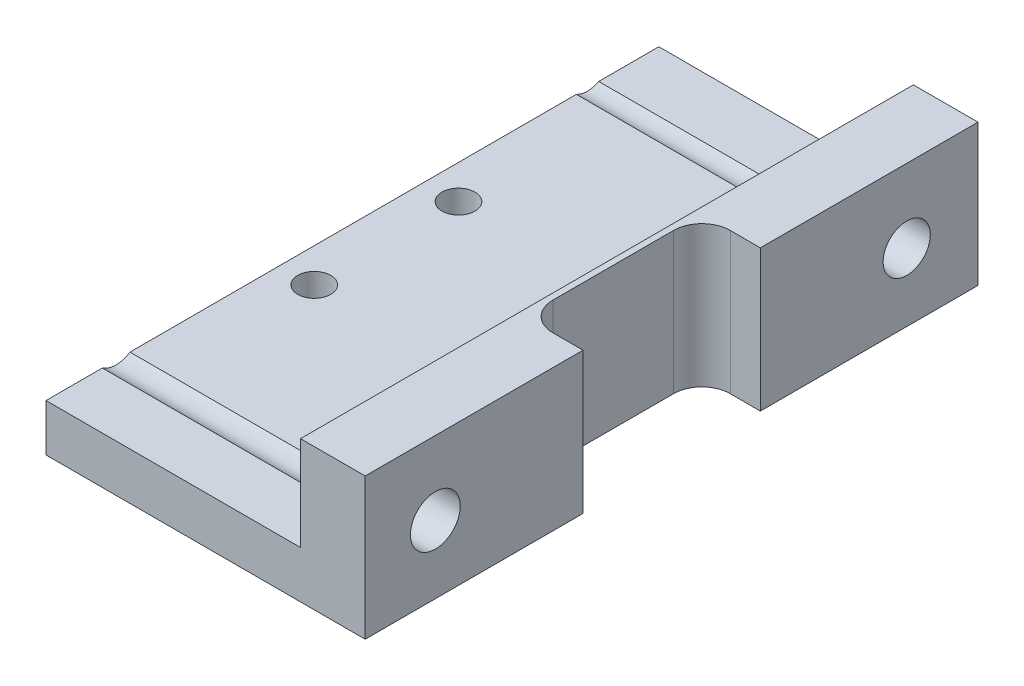
SolidWorks part; units mm, degrees
ref_plane "Alzado" through (0, 0, 0) normal (0, 0, 1) x (1, 0, 0)
ref_plane "Planta" through (0, 0, 0) normal (0, 1, 0) x (1, 0, 0)
ref_plane "Vista lateral" through (0, 0, 0) normal (1, 0, 0) x (0, 0, -1)
sketch "Croquis1" plane through (0, 0, 0) normal (0, 1, 0) x (1, 0, 0)
  line L0 (10.6725, -9.7621) -> (7.4725, -9.7621)
  line L1 (-23.1831, 32.1331) -> (10.6725, 32.1331)
  line L2 (-23.1831, 32.1331) -> (-23.1831, -32.8682)
  line L3 (-23.1831, -32.8682) -> (10.6725, -32.8682)
  line L4 (10.6725, 32.1331) -> (10.6725, 9.0402)
  line L5 (4.4725, -6.7621) -> (4.4725, 6.0505)
  line L6 (7.4822, 9.0505) -> (10.6725, 9.0402)
  line L7 (10.6725, -9.7621) -> (10.6725, -32.8682)
  arc A0 (7.4822, 9.0505) -> (4.4725, 6.0505) centre (7.4725, 6.0505) ccw
  arc A1 (4.4725, -6.7621) -> (7.4725, -9.7621) centre (7.4725, -6.7621) ccw
  dimension "D1" = 3
extrude "Saliente-Extruir1" add sketch "Croquis1" along normal blind 15
sketch "Croquis2" plane through (0, 0, 0) normal (0, -1, 0) x (1, 0, 0)
  line L0 (-23.1831, -32.1331) -> (-23.1831, 32.8682) construction
  line L1 (-23.1831, 0.3676) -> (19.7756, 0.3676) construction
  line L3 (3.8169, -17.1324) -> (-23.1831, -17.1324)
  line L4 (3.8169, -17.1324) -> (3.8169, 17.8676)
  line L5 (3.8169, 17.8676) -> (-23.1831, 17.8676)
  line L6 (-23.1831, -17.1324) -> (-23.1831, 17.8676)
  line L7 (3.8169, -17.1324) -> (-23.1831, 17.8676) construction
  line L8 (3.8169, 17.8676) -> (-23.1831, -17.1324) construction
  circle A0 centre (0.4169, -7.2824) radius 1.75
  circle A1 centre (-19.5831, -7.2824) radius 1.75
  circle A2 centre (-19.5831, 8.0176) radius 1.75
  circle A3 centre (0.4169, 8.0176) radius 1.75
  point P6 (-9.6831, 0.3676)
  dimension "D6" = 3.5
  dimension "D7" = 3.5
  dimension "D1" = 35
  dimension "D2" = 27
  dimension "D3" = 3.4
  dimension "D4" = 9.85
  dimension "D5" = 20
sketch "Croquis3" plane through (0, 0, -32.1331) normal (0, 0, -1) x (-1, 0, 0)
  line L1 (23.1831, 15) -> (-3.8169, 15)
  line L2 (23.1831, 15) -> (23.1831, 5)
  line L3 (23.1831, 5) -> (-3.8169, 5)
  line L4 (-3.8169, 15) -> (-3.8169, 5)
  dimension "D1" = 27
  dimension "D2" = 10
extrude "Cortar-Extruir1" cut sketch "Croquis3" against normal blind 103
extrude "Cortar-Extruir2" cut sketch "Croquis2" against normal blind 25.85 contours A3 | A0 | A2 | A1
sketch "Croquis4" plane through (10.6725, 0, 0) normal (1, 0, 0) x (0, 0, -1)
  circle A0 centre (24.574, 7.2017) radius 2.5
  circle A1 centre (-25.426, 7.2017) radius 2.6437
extrude "Cortar-Extruir3" cut sketch "Croquis4" against normal blind 34
